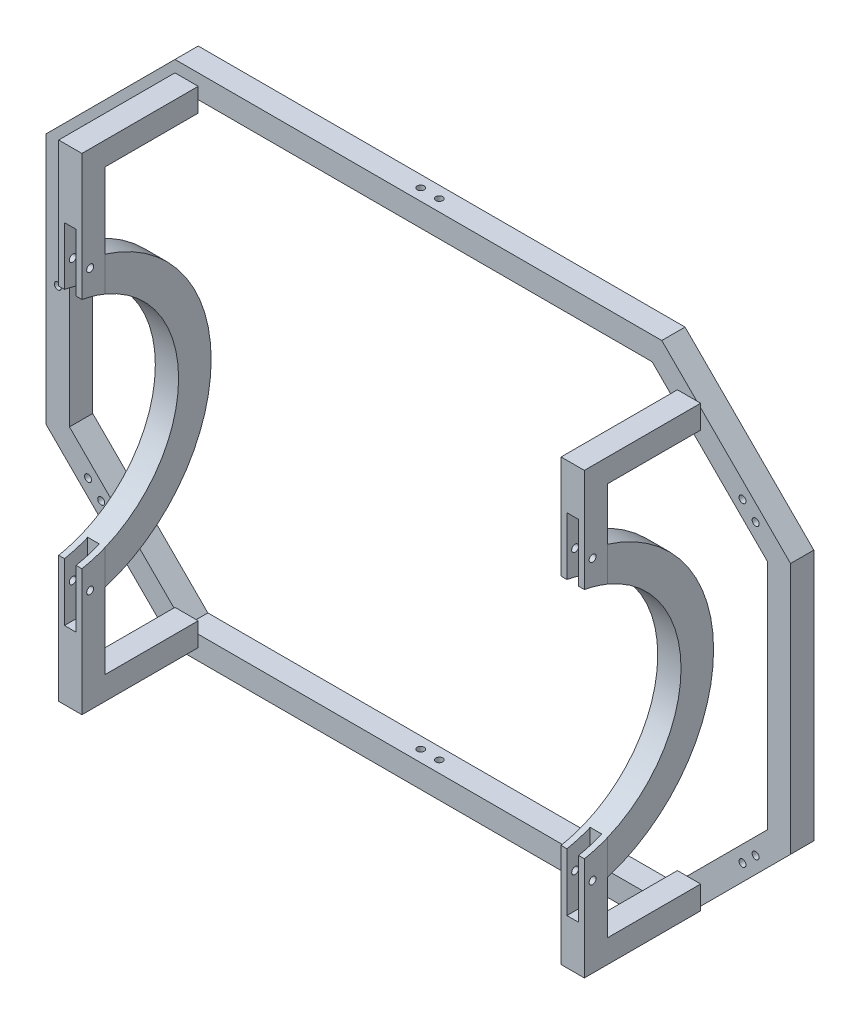
SolidWorks part; units mm, degrees
material "6063-O"
ref_plane "Ön Düzlem" through (0, 0, 0) normal (0, 0, 1) x (1, 0, 0)
ref_plane "Üst Düzlem" through (0, 0, 0) normal (0, 1, 0) x (1, 0, 0)
ref_plane "Sağ Düzlem" through (0, 0, 0) normal (1, 0, 0) x (0, 0, -1)
sketch "Çizim1" plane through (0, 0, 0) normal (0, 0, 1) x (1, 0, 0)
  line L0 (-150, 50) -> (-150, -50)
  line L1 (-150, -50) -> (-100.5025, -99.4975)
  line L3 (-150, 50) -> (-100.5025, 99.4975)
  line L6 (-160, 54.1421) -> (-104.6447, 109.4975)
  line L10 (-160, -54.1421) -> (-104.6447, -109.4975)
  line L11 (-160, 54.1421) -> (-160, -54.1421)
  line L12 (136.5685, 0) -> (-160, 0) construction
  line L13 (0, 0) -> (0, 45.7786) construction
  line L14 (119.4975, 99.4975) -> (119.4975, -99.4975) construction
  line L15 (-104.6447, 109.4975) -> (129.4975, 109.4975) construction
  line L16 (-100.5025, 99.4975) -> (119.4975, 99.4975) construction
  line L17 (129.4975, 109.4975) -> (129.4975, -109.4975) construction
  line L18 (-100.5025, -99.4975) -> (119.4975, -99.4975) construction
  line L19 (-104.6447, -109.4975) -> (129.4975, -109.4975) construction
  line L20 (-104.6447, 109.4975) -> (104.6447, 109.4975)
  line L21 (-104.6447, -109.4975) -> (104.6447, -109.4975)
  line L22 (100.5025, 99.4975) -> (-100.5025, 99.4975)
  line L23 (160, 54.1421) -> (160, -54.1421)
  line L24 (100.5025, -99.4975) -> (-100.5025, -99.4975)
  line L25 (160, -54.1421) -> (104.6447, -109.4975)
  line L26 (160, 54.1421) -> (104.6447, 109.4975)
  line L27 (150, 50) -> (100.5025, 99.4975)
  line L28 (150, -50) -> (100.5025, -99.4975)
  line L29 (150, 50) -> (150, -50)
  point P17 (-160, 0)
  point P27 (0, 109.4975)
  point P28 (0, -99.4975)
  point P29 (0, 99.4975)
  point P30 (0, -109.4975)
  dimension "D1" = 45
  dimension "D2" = 45
  dimension "D3" = 100
  dimension "D4" = 70
  dimension "D7" = 160
  dimension "D8" = 49.4975
  dimension "D6" = 10
extrude "Yükseklik-Ekstrüzyon2" add sketch "Çizim1" along normal blind 10
ref_plane "Düzlem1" through (0, -104.5, 0) normal (0, 1, 0) x (1, 0, 0)
sketch "Çizim3" plane through (0, -104.5, 0) normal (0, 1, 0) x (1, 0, 0)
  line L0 (-104.6447, -10) -> (-104.6447, -50)
  line L2 (-160, -10) -> (-104.6447, -10) construction
  line L3 (-94.6447, -10) -> (-94.6447, -50)
  line L4 (-104.6447, -50) -> (-94.6447, -50)
  line L5 (-104.6447, -10) -> (-104.6447, -50) construction
  line L6 (-104.6447, -10) -> (-94.6447, -10)
  point P6 (0, 0)
  dimension "D2" = 40
  dimension "D1" = 10
extrude "Yükseklik-Ekstrüzyon3" add sketch "Çizim3" along normal blind 10
ref_plane "Düzlem2" through (0, 0, 50) normal (0, 0, 1) x (1, 0, 0)
sketch "Çizim4" plane through (0, 0, 50) normal (0, 0, 1) x (1, 0, 0)
  line L0 (27.5, -104.5) -> (-27.5, -104.5) construction
  line L2 (-94.6447, 0) -> (-94.6447, -94.5)
  line L4 (-104.6447, 0) -> (-104.6447, -94.5)
  line L5 (-104.6447, -94.5) -> (-104.6447, -104.5)
  line L6 (-94.6447, -104.5) -> (-94.6447, -94.5)
  line L7 (-104.6447, -94.5) -> (-104.6447, -104.5) construction
  line L8 (-94.6447, 0) -> (-104.6447, 0)
  line L9 (-104.6447, -94.5) -> (-104.6447, -104.5) construction
  line L11 (-104.6447, -94.5) -> (-94.6447, -94.5) construction
  line L19 (-104.6447, -104.5) -> (-94.6447, -104.5)
  line L20 (-94.6447, -104.5) -> (-94.6447, -94.5)
  line L21 (-94.6447, -94.5) -> (-104.6447, -94.5)
  line L22 (-104.6447, -94.5) -> (-104.6447, -104.5)
  line L23 (-104.6447, -104.5) -> (-94.6447, -104.5)
  line L24 (-94.6447, -104.5) -> (-94.6447, -94.5)
  line L26 (-104.6447, -94.5) -> (-104.6447, -104.5)
  point P0 (-19.5864, 0)
  dimension "D2" = 0
extrude "Yükseklik-Ekstrüzyon4" add sketch "Çizim4" along normal blind 10
ref_plane "Düzlem3" through (0, -94.5, 0) normal (0, 1, 0) x (1, 0, 0)
sketch "Çizim6" plane through (0, -94.5, 0) normal (0, 1, 0) x (1, 0, 0)
  line L13 (111.3553, -10) -> (111.3553, -60)
  line L14 (104.6447, -10) -> (160, -10) construction
  line L15 (111.3553, -60) -> (121.3553, -60)
  line L16 (121.3553, -60) -> (121.3553, -10)
  line L17 (121.3553, -10) -> (111.3553, -10)
  line L18 (-104.6447, -10) -> (-104.6447, -50) construction
  dimension "D1" = 226
  dimension "D2" = 10
  dimension "D3" = 50
extrude "Yükseklik-Ekstrüzyon5" add sketch "Çizim6" along normal blind 10
sketch "Çizim7" plane through (0, 0, 50) normal (0, 0, 1) x (1, 0, 0)
  line L0 (121.3553, -94.5) -> (121.3553, 0)
  line L1 (121.3553, 0) -> (111.3553, 0)
  line L2 (121.3553, -94.5) -> (111.3553, -94.5)
  line L3 (111.3553, -94.5) -> (111.3553, 0)
  line L4 (111.3553, -84.5) -> (121.3553, -84.5) construction
  point P4 (116.3553, -84.5)
  point P7 (116.3553, -94.5)
extrude "Yükseklik-Ekstrüzyon6" add sketch "Çizim7" along normal blind 10
mirror "Aynalama1" about plane through (0, 0, 0) normal (0, 1, 0) of "Yükseklik-Ekstrüzyon4", "Yükseklik-Ekstrüzyon5", "Yükseklik-Ekstrüzyon3", "Yükseklik-Ekstrüzyon6"
sketch "Çizim8" plane through (0, 0, 10) normal (0, 0, 1) x (1, 0, 0)
  line L0 (-150, 0) -> (-160, 0) construction
  line L1 (-160, -54.1421) -> (-104.6447, -109.4975) construction
  line L2 (-150, 50) -> (-150, -50) construction
  line L3 (-160, 54.1421) -> (-160, -54.1421) construction
  line L5 (160, 54.1421) -> (121.3553, 92.7868) construction
  line L8 (100.5025, -99.4975) -> (111.3553, -88.6447) construction
  line L9 (-104.6447, 109.4975) -> (-160, 54.1421) construction
  circle A4 centre (145, 62.0711) radius 1.5
  circle A5 centre (139.3431, 67.7279) radius 1.5
  circle A6 centre (139.3431, -67.7279) radius 1.5
  circle A7 centre (145, -62.0711) radius 1.5
  circle A12 centre (-136.3431, 70.7279) radius 1.5
  circle A13 centre (-142, 65.0711) radius 1.5
  circle A14 centre (-136.3431, -70.7279) radius 1.5
  circle A15 centre (-142, -65.0711) radius 1.5
  circle A16 centre (-155, 0) radius 1.5
  dimension "D4" = 3
  dimension "D5" = 8
  dimension "D7" = 5
  dimension "D11" = 3
  dimension "D14" = 8
  dimension "D15" = 3
  dimension "D19" = 5
  dimension "D27" = 3
  dimension "D28" = 3
  dimension "D22" = 3
  dimension "D3" = 8
  dimension "D6" = 5
  dimension "D8" = 5
  dimension "D9" = 8
  dimension "D10" = 8
  dimension "D12" = 5
  dimension "D13" = 5
  dimension "D16" = 5
  dimension "D17" = 5
  dimension "D18" = 5
  dimension "D20" = 5
  dimension "D21" = 50
  dimension "D26" = 8
extrude "Kes-Ekstrüzyon1" cut sketch "Çizim8" against normal blind 35
sketch "Çizim9" plane through (0, -94.5, 0) normal (0, 1, 0) x (1, 0, 0)
  circle A0 centre (-4, -4.9928) radius 1.5
  circle A1 centre (4, -4.9928) radius 1.5
  dimension "D2" = 3
  dimension "D1" = 4
  dimension "D3" = 8
extrude "Kes-Ekstrüzyon2" cut sketch "Çizim9" along normal mid plane 531
ref_plane "Düzlem4" through (-99.64, 0, 0) normal (1, 0, 0) x (0, 0, -1)
sketch "Çizim12" plane through (-99.64, 0, 0) normal (1, 0, 0) x (0, 0, -1)
  circle A0 centre (-69.4435, 0) radius 51
  point P0 (-69.4435, 0)
  dimension "D1" = 102
ref_plane "Düzlem5" through (116.36, 0, 0) normal (1, 0, 0) x (0, 0, -1)
extrude "Kes-Ekstrüzyon4" cut sketch "Çizim12" against normal mid plane 676
sketch "Çizim19" plane through (-99.64, 0, 0) normal (1, 0, 0) x (0, 0, -1)
  line L4 (-50, -62.0238) -> (-50, -47.1482)
  line L5 (-50, 62.0238) -> (-50, 47.1482)
  arc A1 (-50, -62.0238) -> (-50, 62.0238) centre (-69.4435, 0) ccw
  arc A2 (-50, -47.1482) -> (-50, 47.1482) centre (-69.4435, 0) ccw
  dimension "D2" = 130
extrude "Yükseklik-Ekstrüzyon7" add sketch "Çizim19" along normal mid plane 10
sketch "Çizim20" plane through (116.36, 0, 0) normal (1, 0, 0) x (0, 0, -1)
  line L2 (-50, -47.1482) -> (-50, -62.0238)
  line L12 (-50, -47.1482) -> (-50, -62.0238)
  line L14 (-50, 62.0238) -> (-50, 47.1482)
  line L15 (-50, 62.0238) -> (-50, 47.1482)
  arc A2 (-50, -62.0238) -> (-50, 62.0238) centre (-69.4435, 0) ccw
  arc A3 (-50, -47.1482) -> (-50, 47.1482) centre (-69.4435, 0) ccw
  arc A4 (-50, -62.0238) -> (-50, 62.0238) centre (-69.4435, 0) ccw
  arc A5 (-50, -47.1482) -> (-50, 47.1482) centre (-69.4435, 0) ccw
  dimension "D1" = 0
extrude "Yükseklik-Ekstrüzyon8" add sketch "Çizim20" along normal mid plane 10
sketch "Çizim21" plane through (-99.64, 0, 0) normal (1, 0, 0) x (0, 0, -1)
  line L5 (-50, 125.95) -> (-50, -125.95) construction
  line L6 (-63.2751, 75) -> (-50, 75)
  line L7 (-63.2751, 75) -> (-63.2751, -75)
  line L8 (-63.2751, -75) -> (-50, -75)
  line L9 (-50, 75) -> (-50, -75)
  line L10 (-63.2751, 75) -> (-50, -75) construction
  line L11 (-63.2751, -75) -> (-50, 75) construction
  point P0 (-56.6376, 0)
  dimension "D1" = 150
extrude "Kes-Ekstrüzyon5" cut sketch "Çizim21" against normal mid plane 5
sketch "Çizim22" plane through (116.36, 0, 0) normal (1, 0, 0) x (0, 0, -1)
  line L5 (-50, 218.9949) -> (-50, -104.5) construction
  line L6 (-65.4707, 75) -> (-50, 75)
  line L7 (-65.4707, 75) -> (-65.4707, -75)
  line L8 (-65.4707, -75) -> (-50, -75)
  line L9 (-50, 75) -> (-50, -75)
  line L10 (-65.4707, 75) -> (-50, -75) construction
  line L11 (-65.4707, -75) -> (-50, 75) construction
  point P0 (-57.7354, 0)
  dimension "D1" = 150
extrude "Kes-Ekstrüzyon6" cut sketch "Çizim22" against normal mid plane 5
sketch "Çizim23" plane through (-99.64, 0, 0) normal (1, 0, 0) x (0, 0, -1)
  circle A0 centre (-56.4435, 60) radius 1.5
  arc A1 (-50, -47.1482) -> (-50, 47.1482) centre (-69.4435, 0) ccw construction
  circle A2 centre (-56.4435, -60) radius 1.5
  dimension "D1" = 13
  dimension "D2" = 3
  dimension "D3" = 3
  dimension "D4" = 120
  dimension "D5" = 60
extrude "Kes-Ekstrüzyon7" cut sketch "Çizim23" against normal mid plane 484
